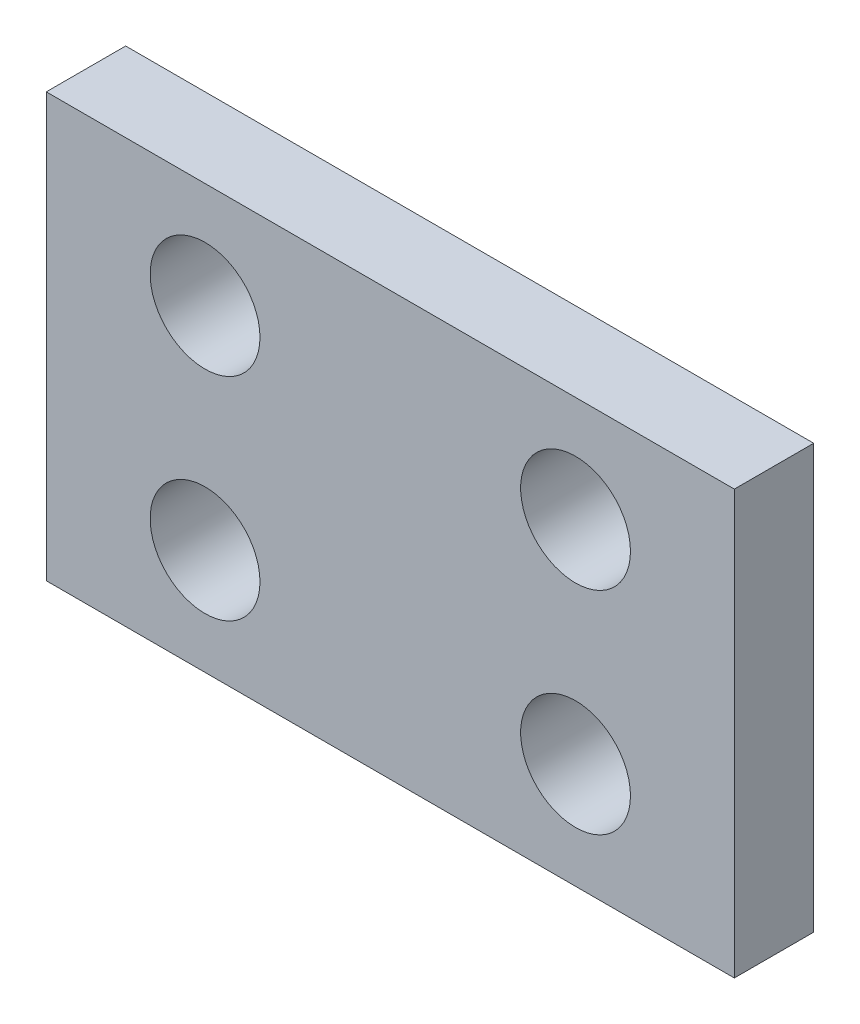
SolidWorks part; units mm, degrees
material "Thornel VCB-20 碳布"
ref_plane "前视基准面" through (0, 0, 0) normal (0, 0, 1) x (1, 0, 0)
ref_plane "上视基准面" through (0, 0, 0) normal (0, 1, 0) x (1, 0, 0)
ref_plane "右视基准面" through (0, 0, 0) normal (1, 0, 0) x (0, 0, -1)
other "Configuration Table"
sketch "草图1" plane through (0, 0, 0) normal (0, 0, 1) x (1, 0, 0)
  line L1 (0, 0) -> (26, 0)
  line L2 (0, 0) -> (0, 16)
  line L3 (0, 16) -> (26, 16)
  line L4 (26, 0) -> (26, 16)
  dimension "D1" = 16
  dimension "D2" = 26
extrude "凸台-拉伸1" add sketch "草图1" along normal blind 3
sketch "草图2" plane through (0, 0, 3) normal (0, 0, 1) x (1, 0, 0)
  line L0 (0, 8) -> (26, 8) construction
  line L1 (0, 16) -> (0, 0) construction
  line L2 (26, 0) -> (26, 16) construction
  line L3 (26, 16) -> (0, 16) construction
  line L4 (6, 12) -> (20, 12) construction
  line L5 (6, 12) -> (6, 4) construction
  line L6 (6, 4) -> (20, 4) construction
  line L7 (20, 12) -> (20, 4) construction
  circle A0 centre (6, 12) radius 2.075
  circle A1 centre (20, 12) radius 2.075
  circle A2 centre (6, 4) radius 2.075
  circle A3 centre (20, 4) radius 2.075
  point P6 (0, 8)
  point P15 (20.4465, 12.1218)
  dimension "D1" = 4.15
  dimension "D2" = 14
  dimension "D3" = 6
  dimension "D4" = 8
  dimension "D5" = 4
extrude "切除-拉伸1" cut sketch "草图2" against normal blind 3
